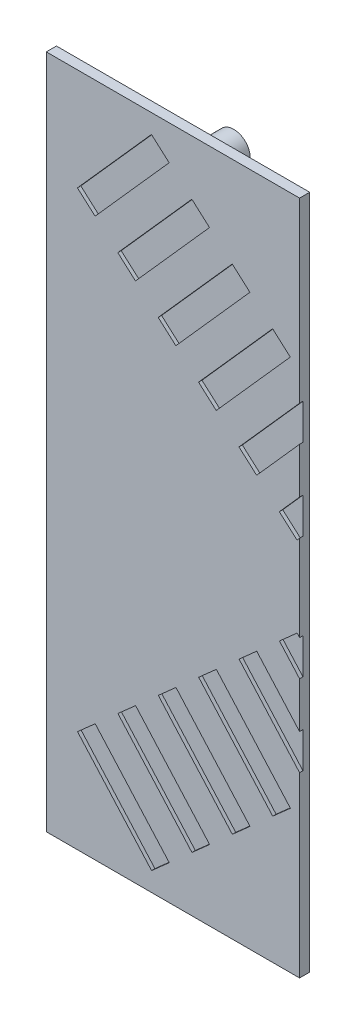
SolidWorks part; units mm, degrees
ref_plane "Front Plane" through (0, 0, 0) normal (0, 0, 1) x (1, 0, 0)
ref_plane "Top Plane" through (0, 0, 0) normal (0, 1, 0) x (1, 0, 0)
ref_plane "Right Plane" through (0, 0, 0) normal (1, 0, 0) x (0, 0, -1)
sketch "Sketch1" plane through (0, 0, 0) normal (0, 0, 1) x (1, 0, 0)
  line L1 (0, 0) -> (225, 0)
  line L2 (0, 0) -> (0, 200)
  line L3 (0, 200) -> (225, 200)
  line L4 (225, 0) -> (225, 200)
  dimension "D1" = 225
  dimension "D2" = 200
extrude "Boss-Extrude1" add sketch "Sketch1" along normal blind 3
sketch "Sketch2" plane through (0, 0, 3) normal (0, 0, 1) x (1, 0, 0)
  line L0 (0, 200) -> (225, 0) construction
  line L1 (225, 200) -> (0, 0) construction
  line L2 (21.1766, 159.1001) -> (43.1006, 183.7646)
  line L3 (9.218, 169.7299) -> (31.1421, 194.3944)
  line L4 (9.218, 169.7299) -> (14.4499, 165.0794)
  line L5 (14.4499, 165.0794) -> (36.3739, 189.7439)
  line L6 (31.1421, 194.3944) -> (36.3739, 189.7439)
  line L7 (21.1766, 159.1001) -> (26.4085, 154.4496)
  line L8 (26.4085, 154.4496) -> (48.3325, 179.1141)
  line L9 (43.1006, 183.7646) -> (48.3325, 179.1141)
  line L10 (33.1351, 148.4703) -> (55.0592, 173.1348)
  line L11 (33.1351, 148.4703) -> (38.367, 143.8197)
  line L12 (38.367, 143.8197) -> (60.291, 168.4842)
  line L13 (55.0592, 173.1348) -> (60.291, 168.4842)
  line L14 (45.0937, 137.8405) -> (67.0177, 162.505)
  line L15 (45.0937, 137.8405) -> (50.3256, 133.1899)
  line L16 (50.3256, 133.1899) -> (72.2496, 157.8544)
  line L17 (67.0177, 162.505) -> (72.2496, 157.8544)
  line L18 (57.0522, 127.2106) -> (78.9763, 151.8751)
  line L19 (57.0522, 127.2106) -> (62.2841, 122.5601)
  line L20 (62.2841, 122.5601) -> (84.2081, 147.2246)
  line L21 (78.9763, 151.8751) -> (84.2081, 147.2246)
  line L22 (69.0108, 116.5808) -> (90.9348, 141.2453)
  line L23 (69.0108, 116.5808) -> (74.2427, 111.9303)
  line L24 (74.2427, 111.9303) -> (96.1667, 136.5948)
  line L25 (90.9348, 141.2453) -> (96.1667, 136.5948)
  line L26 (80.9693, 105.951) -> (102.8933, 130.6155)
  line L27 (80.9693, 105.951) -> (86.2012, 101.3004)
  line L28 (86.2012, 101.3004) -> (108.1252, 125.965)
  line L29 (102.8933, 130.6155) -> (108.1252, 125.965)
  line L38 (116.845, 74.0615) -> (138.769, 98.726)
  line L39 (116.845, 74.0615) -> (122.0769, 69.411)
  line L40 (122.0769, 69.411) -> (144.0009, 94.0755)
  line L41 (138.769, 98.726) -> (144.0009, 94.0755)
  line L42 (128.8035, 63.4317) -> (150.7275, 88.0962)
  line L43 (128.8035, 63.4317) -> (134.0354, 58.7812)
  line L44 (134.0354, 58.7812) -> (155.9594, 83.4457)
  line L45 (150.7275, 88.0962) -> (155.9594, 83.4457)
  line L46 (140.7621, 52.8019) -> (162.6861, 77.4664)
  line L47 (140.7621, 52.8019) -> (145.994, 48.1513)
  line L48 (145.994, 48.1513) -> (167.918, 72.8158)
  line L49 (162.6861, 77.4664) -> (167.918, 72.8158)
  line L50 (152.7206, 42.1721) -> (174.6446, 66.8366)
  line L51 (152.7206, 42.1721) -> (157.9525, 37.5215)
  line L52 (157.9525, 37.5215) -> (179.8765, 62.186)
  line L53 (174.6446, 66.8366) -> (179.8765, 62.186)
  line L54 (164.6792, 31.5422) -> (186.6032, 56.2068)
  line L55 (164.6792, 31.5422) -> (169.9111, 26.8917)
  line L56 (169.9111, 26.8917) -> (191.8351, 51.5562)
  line L57 (186.6032, 56.2068) -> (191.8351, 51.5562)
  line L58 (176.6377, 20.9124) -> (198.5617, 45.5769)
  line L59 (176.6377, 20.9124) -> (181.8696, 16.2619)
  line L60 (181.8696, 16.2619) -> (203.7936, 40.9264)
  line L61 (198.5617, 45.5769) -> (203.7936, 40.9264)
  line L62 (188.5963, 10.2826) -> (210.5203, 34.9471)
  line L63 (188.5963, 10.2826) -> (193.8281, 5.6321)
  line L64 (193.8281, 5.6321) -> (215.7522, 30.2966)
  line L65 (210.5203, 34.9471) -> (215.7522, 30.2966)
  line L66 (198.5915, 154.4496) -> (176.6675, 179.1141)
  line L67 (210.5501, 165.0794) -> (188.6261, 189.7439)
  line L68 (210.5501, 165.0794) -> (215.782, 169.7299)
  line L69 (215.782, 169.7299) -> (193.8579, 194.3944)
  line L70 (188.6261, 189.7439) -> (193.8579, 194.3944)
  line L71 (198.5915, 154.4496) -> (203.8234, 159.1001)
  line L72 (203.8234, 159.1001) -> (181.8994, 183.7646)
  line L73 (176.6675, 179.1141) -> (181.8994, 183.7646)
  line L74 (186.633, 143.8197) -> (164.709, 168.4842)
  line L75 (186.633, 143.8197) -> (191.8649, 148.4703)
  line L76 (191.8649, 148.4703) -> (169.9408, 173.1348)
  line L77 (164.709, 168.4842) -> (169.9408, 173.1348)
  line L78 (174.6744, 133.1899) -> (152.7504, 157.8544)
  line L79 (174.6744, 133.1899) -> (179.9063, 137.8405)
  line L80 (179.9063, 137.8405) -> (157.9823, 162.505)
  line L81 (152.7504, 157.8544) -> (157.9823, 162.505)
  line L82 (162.7159, 122.5601) -> (140.7919, 147.2246)
  line L83 (162.7159, 122.5601) -> (167.9478, 127.2106)
  line L84 (167.9478, 127.2106) -> (146.0237, 151.8751)
  line L85 (140.7919, 147.2246) -> (146.0237, 151.8751)
  line L86 (150.7573, 111.9303) -> (128.8333, 136.5948)
  line L87 (150.7573, 111.9303) -> (155.9892, 116.5808)
  line L88 (155.9892, 116.5808) -> (134.0652, 141.2453)
  line L89 (128.8333, 136.5948) -> (134.0652, 141.2453)
  line L90 (138.7988, 101.3004) -> (116.8748, 125.965)
  line L91 (138.7988, 101.3004) -> (144.0307, 105.951)
  line L92 (144.0307, 105.951) -> (122.1067, 130.6155)
  line L93 (116.8748, 125.965) -> (122.1067, 130.6155)
  line L102 (102.9231, 69.411) -> (80.9991, 94.0755)
  line L103 (102.9231, 69.411) -> (108.155, 74.0615)
  line L104 (108.155, 74.0615) -> (86.231, 98.726)
  line L105 (80.9991, 94.0755) -> (86.231, 98.726)
  line L106 (90.9646, 58.7812) -> (69.0406, 83.4457)
  line L107 (90.9646, 58.7812) -> (96.1965, 63.4317)
  line L108 (96.1965, 63.4317) -> (74.2725, 88.0962)
  line L109 (69.0406, 83.4457) -> (74.2725, 88.0962)
  line L110 (79.006, 48.1513) -> (57.082, 72.8158)
  line L111 (79.006, 48.1513) -> (84.2379, 52.8019)
  line L112 (84.2379, 52.8019) -> (62.3139, 77.4664)
  line L113 (57.082, 72.8158) -> (62.3139, 77.4664)
  line L114 (67.0475, 37.5215) -> (45.1235, 62.186)
  line L115 (67.0475, 37.5215) -> (72.2794, 42.1721)
  line L116 (72.2794, 42.1721) -> (50.3554, 66.8366)
  line L117 (45.1235, 62.186) -> (50.3554, 66.8366)
  line L118 (55.0889, 26.8917) -> (33.1649, 51.5562)
  line L119 (55.0889, 26.8917) -> (60.3208, 31.5422)
  line L120 (60.3208, 31.5422) -> (38.3968, 56.2068)
  line L121 (33.1649, 51.5562) -> (38.3968, 56.2068)
  line L122 (43.1304, 16.2619) -> (21.2064, 40.9264)
  line L123 (43.1304, 16.2619) -> (48.3623, 20.9124)
  line L124 (48.3623, 20.9124) -> (26.4383, 45.5769)
  line L125 (21.2064, 40.9264) -> (26.4383, 45.5769)
  line L126 (31.1719, 5.6321) -> (9.2478, 30.2966)
  line L127 (31.1719, 5.6321) -> (36.4037, 10.2826)
  line L128 (36.4037, 10.2826) -> (14.4797, 34.9471)
  line L129 (9.2478, 30.2966) -> (14.4797, 34.9471)
  line L130 (92.9279, 95.3212) -> (114.8519, 119.9857) [skipped]
  line L131 (98.1598, 90.6706) -> (120.0838, 115.3351) [skipped]
  line L132 (114.8519, 119.9857) -> (120.0838, 115.3351) [skipped]
  line L133 (126.8402, 90.6706) -> (104.9162, 115.3351) [skipped]
  line L134 (132.0721, 95.3212) -> (110.1481, 119.9857) [skipped]
  line L135 (104.9162, 115.3351) -> (110.1481, 119.9857) [skipped]
  line L136 (104.8864, 84.6914) -> (126.8104, 109.3559) [skipped]
  line L137 (104.8864, 84.6914) -> (110.1183, 80.0408) [skipped]
  line L138 (110.1183, 80.0408) -> (132.0423, 104.7053) [skipped]
  line L139 (114.8817, 80.0408) -> (92.9577, 104.7053) [skipped]
  line L140 (114.8817, 80.0408) -> (120.1136, 84.6914) [skipped]
  line L141 (120.1136, 84.6914) -> (98.1896, 109.3559) [skipped]
  line L142 (126.8402, 90.6706) -> (132.0721, 95.3212) [skipped]
  line L143 (126.8104, 109.3559) -> (132.0423, 104.7053) [skipped]
  line L144 (92.9577, 104.7053) -> (98.1896, 109.3559) [skipped]
  line L145 (92.9279, 95.3212) -> (98.1598, 90.6706) [skipped]
  point P12 (20.1801, 182.0622)
  point P79 (199.5881, 177.4116)
  dimension "D1" = 33
  dimension "D2" = 7
  dimension "D3" = 33
  dimension "D5" = 27
  dimension "D6" = 33
  dimension "D7" = 7
  dimension "D8" = 33
  dimension "D9" = 27
  dimension "D4" = 16
  dimension "D10" = 16
extrude "Cut-Extrude1" cut sketch "Sketch2" against normal blind 1
sketch "Sketch4" plane through (0, 0, 0) normal (0, 0, -1) x (-1, 0, 0)
  line L0 (0, 200) -> (0, 0) construction
  line L1 (-212.5, 200) -> (-12.5, 200)
  line L2 (-212.5, 200) -> (-212.5, 0)
  line L3 (-212.5, 0) -> (-12.5, 0)
  line L4 (-12.5, 200) -> (-12.5, 0)
  line L5 (0, 0) -> (-225, 0) construction
  line L7 (0, 200) -> (-75, 200)
  line L8 (0, 200) -> (0, 0)
  line L9 (-225, 200) -> (-150, 200)
  line L10 (-225, 200) -> (-225, 0)
  line L11 (-225, 0) -> (-150, 0)
  line L12 (-150, 200) -> (-150, 0)
  line L13 (0, 0) -> (-75, 0)
  line L14 (-75, 200) -> (-75, 0)
  circle A0 centre (-202.5, 190) radius 4.9
  circle A1 centre (-160, 10) radius 4.9
  circle A2 centre (-122.5, 190) radius 4.9
  circle A3 centre (-102.5, 10) radius 4.9
  circle A4 centre (-42.5, 190) radius 4.9
  circle A5 centre (-22.5, 10) radius 4.9
  point P29 (0, 0)
  dimension "D4" = 10
  dimension "D5" = 9.8
  dimension "D6" = 10
  dimension "D7" = 10
  dimension "D8" = 10
  dimension "D9" = 12.5
  dimension "D1" = 9.8
  dimension "D11" = 80
  dimension "D12" = 20
  dimension "D13" = 20
  dimension "D14" = 80
  dimension "D15" = 9.8
  dimension "D16" = 9.8
  dimension "D17" = 9.8
  dimension "D18" = 9.8
  dimension "D2" = 12.5
  dimension "D3" = 75
  dimension "D10" = 75
extrude "Boss-Extrude2" add sketch "Sketch4" along normal blind 10 contours A4 | A5
sketch "Sketch5" plane through (0, 0, 0) normal (0, 0, -1) x (-1, 0, 0)
  line L0 (0, 0) -> (-225, 0) construction
  line L6 (-225, 200) -> (-75, 200)
  line L7 (-225, 200) -> (-225, 0)
  line L8 (-225, 0) -> (-75, 0)
  line L9 (-75, 200) -> (-75, 0)
  dimension "D2" = 150
extrude "Cut-Extrude2" cut sketch "Sketch5" against normal blind 10
